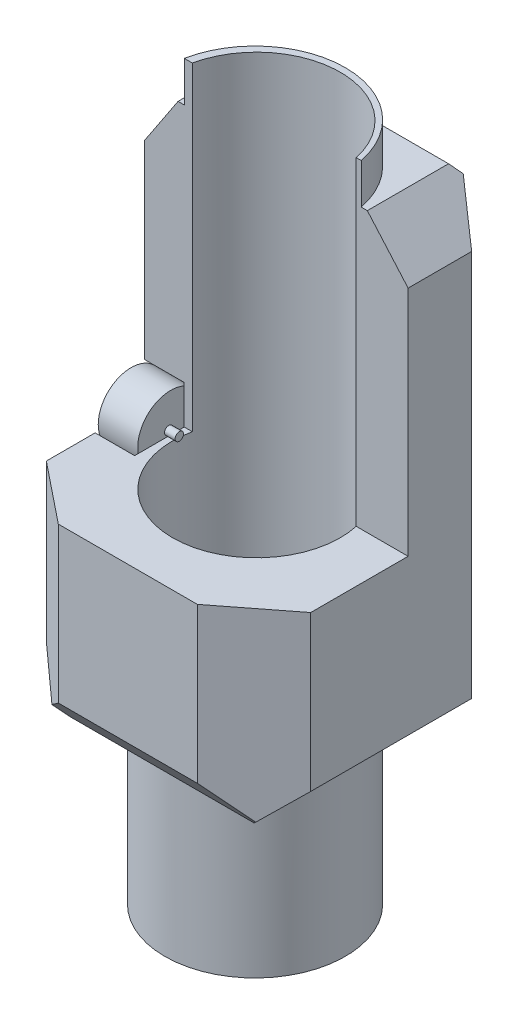
SolidWorks part; units mm, degrees
ref_plane "Front Plane" through (0, 0, 0) normal (0, 0, 1) x (1, 0, 0)
ref_plane "Top Plane" through (0, 0, 0) normal (0, 1, 0) x (1, 0, 0)
ref_plane "Right Plane" through (0, 0, 0) normal (1, 0, 0) x (0, 0, -1)
sketch "Sketch1" plane through (0, 0, 0) normal (0, 1, 0) x (1, 0, 0)
  line L1 (0, 0) -> (-100, 0)
  line L2 (0, 0) -> (0, 100)
  line L3 (0, 100) -> (-100, 100)
  line L4 (-100, 0) -> (-100, 100)
  dimension "D1" = 100
  dimension "D2" = 100
extrude "Boss-Extrude1" add sketch "Sketch1" along normal blind 180
sketch "Sketch2" plane through (0, 180, 0) normal (0, 1, 0) x (1, 0, 0)
  circle A0 centre (-51.3773, 49.0765) radius 34.2578
  point P2 (-49.1037, 52.2166)
  point P3 (-48.8771, 51.8469)
  point P4 (-51.3773, 49.0765)
extrude "Boss-Extrude2" add sketch "Sketch2" along normal mid plane 700
sketch "Sketch3" plane through (0, 0, 0) normal (1, 0, 0) x (0, 0, -1)
  line L1 (-18.5833, 361.0481) -> (133.4231, 361.0481)
  line L2 (-18.5833, 361.0481) -> (-18.5833, 643.5005)
  line L3 (-18.5833, 643.5005) -> (133.4231, 643.5005)
  line L4 (133.4231, 361.0481) -> (133.4231, 643.5005)
extrude "Cut-Extrude2" cut sketch "Sketch3" against normal blind 400
sketch "Sketch4" plane through (0, 0, 0) normal (1, 0, 0) x (0, 0, -1)
  line L0 (12.982, 0) -> (-8.9942, 25.8281)
  line L1 (-8.9942, 25.8281) -> (-18.5645, -15.2595)
  line L2 (-18.5645, -15.2595) -> (12.982, 0)
  line L3 (85.0725, -1.4481) -> (109.2376, 19.1131)
  line L4 (109.2376, 19.1131) -> (115.92, -3.2674)
  line L5 (115.92, -3.2674) -> (85.0725, -1.4481)
  line L6 (12.982, 180) -> (-8.9942, 148.5376)
  line L7 (-8.9942, 148.5376) -> (-15.4182, 193.2193)
  line L8 (-15.4182, 193.2193) -> (12.982, 180)
  line L9 (85.0725, 181.8543) -> (103.8412, 159.7959)
  line L10 (103.8412, 159.7959) -> (106.1325, 198.6474)
  line L11 (106.1325, 198.6474) -> (85.0725, 181.8543)
extrude "Cut-Extrude3" cut sketch "Sketch4" against normal blind 400
sketch "Sketch5" plane through (0, 0, 0) normal (0, 0, 1) x (1, 0, 0)
  line L0 (-85.6233, 0) -> (-106.3704, 21.4264)
  line L1 (-106.3704, 21.4264) -> (-122.2889, 3.2093)
  line L2 (-122.2889, 3.2093) -> (-93.5263, -19.8847)
  line L3 (-93.5263, -19.8847) -> (-85.6233, 0)
  line L4 (-15.695, 0) -> (0, 15.2574)
  line L5 (0, 15.2574) -> (12.1227, 15.2574)
  line L6 (12.1227, 15.2574) -> (10.5631, -19.8847)
  line L7 (10.5631, -19.8847) -> (-15.695, 0)
  line L8 (-87.1665, 180.2481) -> (-106.3704, 151.2911)
  line L9 (-106.3704, 151.2911) -> (-117.7055, 200.5011)
  line L10 (-117.7055, 200.5011) -> (-87.1665, 180.2481)
  line L11 (-15.695, 180.2481) -> (7.8338, 153.2796)
  line L12 (7.8338, 153.2796) -> (0, 193.9412)
  line L13 (0, 193.9412) -> (-15.695, 180.2481)
extrude "Cut-Extrude4" cut sketch "Sketch5" against normal blind 400
sketch "Sketch6" plane through (0, 180, 0) normal (0, 1, 0) x (1, 0, 0)
  line L1 (-112.387, 28.4004) -> (-64.2613, -10.2128)
  line L2 (-112.387, 28.4004) -> (-124.6497, -15.5119)
  line L3 (-124.6497, -15.5119) -> (-84.4064, -15.5119)
  line L4 (-64.2613, -10.2128) -> (-84.4064, -15.5119)
  line L5 (-97.0655, 135.8618) -> (-119.3755, 77.7927)
  line L6 (-97.0655, 135.8618) -> (-66.4287, 110.5752)
  line L7 (-66.4287, 110.5752) -> (-118.0433, 64.3476)
  line L8 (-119.3755, 77.7927) -> (-118.0433, 64.3476)
  line L9 (-24.6964, -21.8158) -> (11.0921, -8.9736)
  line L10 (-24.6964, -21.8158) -> (-38.5316, -11.1392)
  line L11 (-38.5316, -11.1392) -> (17.4283, 32.3938)
  line L12 (11.0921, -8.9736) -> (17.4283, 32.3938)
  line L13 (-17.4455, 140.8044) -> (35.4175, 107.2625)
  line L14 (-17.4455, 140.8044) -> (-31.7244, 103.6253)
  line L15 (-31.7244, 103.6253) -> (9.3055, 72.9964)
  line L16 (35.4175, 107.2625) -> (9.3055, 72.9964)
  point P4 (-17.4455, 140.8044)
  point P5 (-30.2763, 114.984)
  point P6 (35.4175, 107.2625)
  point P19 (-30.6265, 106.484)
  point P20 (-11.2095, 88.3109)
extrude "Cut-Extrude5" cut sketch "Sketch6" against normal blind 400
sketch "Sketch7" plane through (0, 0, 0) normal (0, 0, 1) x (1, 0, 0)
  line L1 (-146.2029, -210.0437) -> (13.9564, -210.0437)
  line L2 (-146.2029, -210.0437) -> (-146.2029, -62.6814)
  line L3 (-146.2029, -62.6814) -> (13.9564, -62.6814)
  line L4 (13.9564, -210.0437) -> (13.9564, -62.6814)
extrude "Cut-Extrude6" cut sketch "Sketch7" against normal blind 400
sketch "Sketch8" plane through (0, 0, 0) normal (0, 0, 1) x (1, 0, 0)
  line L1 (-127.1965, 251.4288) -> (20.1142, 251.4288)
  line L2 (-127.1965, 251.4288) -> (-127.1965, 413.4677)
  line L3 (-127.1965, 413.4677) -> (20.1142, 413.4677)
  line L4 (20.1142, 251.4288) -> (20.1142, 413.4677)
extrude "Cut-Extrude7" cut sketch "Sketch8" against normal blind 400
sketch "Sketch9" plane through (0, 251.4288, 0) normal (0, 1, 0) x (1, 0, 0)
  circle A0 centre (-50.809, 49.032) radius 31.8473
  point P2 (-50.6049, 49.6989)
  point P3 (-51.6378, 48.9774)
  point P4 (-50.809, 49.032)
extrude "Cut-Extrude8" cut sketch "Sketch9" against normal blind 400
sketch "Sketch10" plane through (-100, 0, 0) normal (-1, 0, 0) x (0, 0, 1)
  line L1 (-55.8114, 74.0839) -> (84.4096, 74.0839)
  line L2 (-55.8114, 74.0839) -> (-55.8114, 286.1174)
  line L3 (-55.8114, 286.1174) -> (84.4096, 286.1174)
  line L4 (84.4096, 74.0839) -> (84.4096, 286.1174)
extrude "Cut-Extrude9" cut sketch "Sketch10" against normal blind 400
sketch "Sketch11" plane through (-100, 0, 0) normal (-1, 0, 0) x (0, 0, 1)
  circle A0 centre (-50.4133, 76.2646) radius 13.6031
  point P2 (-50.4133, 76.2646)
extrude "Cut-Extrude11" cut sketch "Sketch11" against normal blind 15
sketch "Sketch12" plane through (-85, 0, 0) normal (-1, 0, 0) x (0, 0, 1)
  circle A0 centre (-50.6588, 76.2225) radius 12.4954
  point P2 (-51.6147, 75.8831)
  point P3 (-50.6588, 76.2225)
extrude "Boss-Extrude3" add sketch "Sketch12" along normal blind 15
sketch "Sketch13" plane through (-85, 0, 0) normal (1, 0, 0) x (0, 0, -1)
  circle A0 centre (49.9452, 75.9448) radius 1.5949
extrude "Boss-Extrude4" add sketch "Sketch13" along normal blind 4
sketch "Sketch14" plane through (-100, 0, 0) normal (-1, 0, 0) x (0, 0, 1)
  line L1 (-115.7243, 195.3259) -> (-14.9757, 195.3259)
  line L2 (-115.7243, 195.3259) -> (-115.7243, 305.8809)
  line L3 (-115.7243, 305.8809) -> (-14.9757, 305.8809)
  line L4 (-14.9757, 195.3259) -> (-14.9757, 305.8809)
extrude "Cut-Extrude13" cut sketch "Sketch14" against normal blind 400
